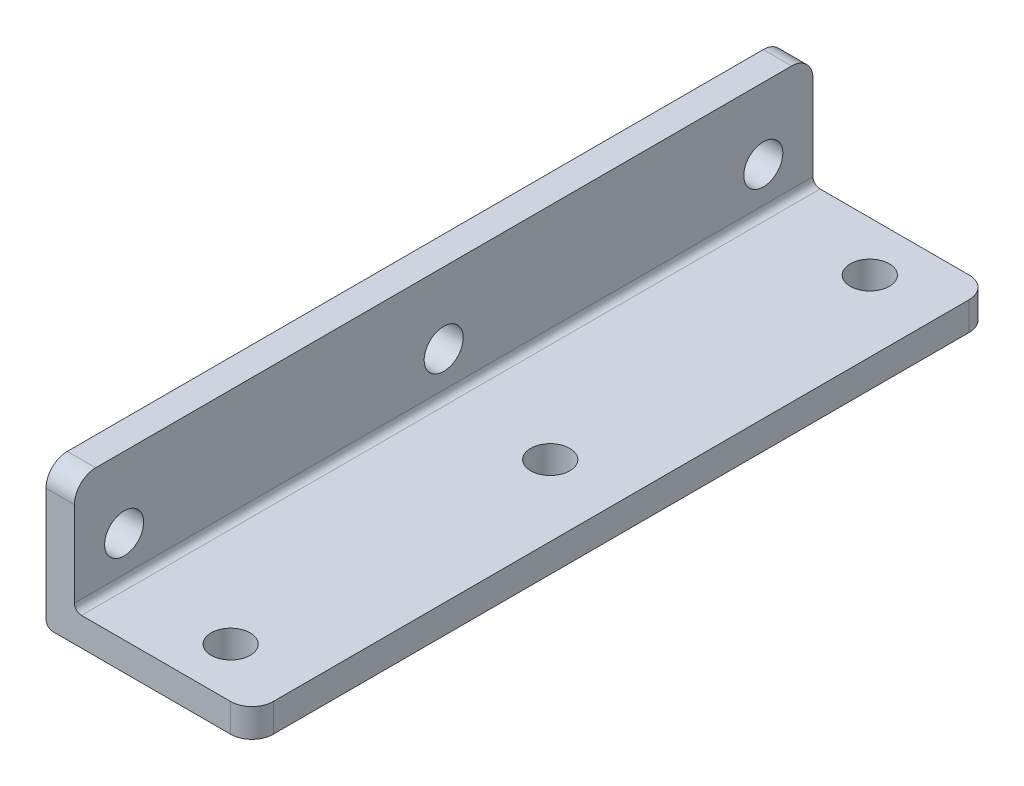
SolidWorks part; units mm, degrees
ref_plane "정면" through (0, 0, 0) normal (0, 0, 1) x (1, 0, 0)
ref_plane "윗면" through (0, 0, 0) normal (0, 1, 0) x (1, 0, 0)
ref_plane "우측면" through (0, 0, 0) normal (1, 0, 0) x (0, 0, -1)
sketch "스케치1" plane through (0, 0, 0) normal (0, 0, 1) x (1, 0, 0)
  line L1 (0, 0) -> (29, 0)
  line L2 (0, 0) -> (0, -4)
  line L3 (0, -4) -> (29, -4)
  line L4 (29, 0) -> (29, -4)
  line L5 (0, 0) -> (4, 0)
  line L6 (0, 0) -> (0, 16)
  line L7 (0, 16) -> (4, 16)
  line L8 (4, 0) -> (4, 16)
  point P8 (29, -2)
  dimension "D1" = 25
  dimension "D2" = 16
  dimension "D3" = 4
  dimension "D4" = 4
extrude "보스-돌출1" add sketch "스케치1" along normal mid plane 110 contours L4 L1 L2 L3 | L1 L8 L7 L6
sketch "스케치2" plane through (0, 0, 0) normal (0, 1, 0) x (1, 0, 0)
  line L0 (19, 55) -> (19, -55) construction
  line L1 (4, 55) -> (29, 55) construction
  line L2 (4, -55) -> (29, -55) construction
  line L3 (4, 0) -> (29, 0) construction
  line L4 (4, -55) -> (4, 55) construction
  line L5 (29, -55) -> (29, 55) construction
  circle A0 centre (19, 0) radius 2.75
  circle A1 centre (19, -45) radius 2.75
  circle A2 centre (19, 45) radius 2.75
  dimension "D1" = 5.5
  dimension "D4" = 5.5
  dimension "D5" = 5.5
  dimension "D2" = 10
  dimension "D3" = 10
  dimension "D6" = 10
sketch "스케치3" plane through (4, 0, 0) normal (1, 0, 0) x (0, 0, -1)
  line L0 (-55, 6) -> (55, 6) construction
  line L3 (0, 16) -> (0, 0) construction
  line L4 (-55, 16) -> (55, 16) construction
  line L5 (-55, 0) -> (55, 0) construction
  line L6 (-55, 0) -> (-55, 16) construction
  line L7 (55, 0) -> (55, 16) construction
  circle A0 centre (0, 6) radius 2.75
  circle A1 centre (-45, 6) radius 2.75
  circle A2 centre (45, 6) radius 2.75
  dimension "D1" = 5.5
  dimension "D2" = 10
extrude "컷-돌출3" cut sketch "스케치3" against normal blind 20
extrude "컷-돌출4" cut sketch "스케치2" against normal blind 20
fillet "필렛2" radius 1 2 edges at (0, -4, 0) (4, 0, 0)
sketch "스케치4" plane through (0, 0, 55) normal (0, 0, 1) x (1, 0, 0)
  line L6 (0, 16) -> (0, -3)
  line L7 (1, -4) -> (29, -4)
  line L8 (29, -4) -> (29, 0)
  line L9 (29, 0) -> (5, 0)
  line L10 (4, 1) -> (4, 16)
  line L11 (4, 16) -> (0, 16)
  line L12 (0, 16) -> (0, -3)
  line L13 (1, -4) -> (29, -4)
  line L14 (29, -4) -> (29, 0)
  line L15 (29, 0) -> (5, 0)
  line L16 (4, 1) -> (4, 16)
  line L17 (4, 16) -> (0, 16)
  arc A2 (0, -3) -> (1, -4) centre (1, -3) ccw
  arc A3 (4, 1) -> (5, 0) centre (5, 1) ccw
  arc A4 (0, -3) -> (1, -4) centre (1, -3) ccw
  arc A5 (4, 1) -> (5, 0) centre (5, 1) ccw
  dimension "D1" = 0
extrude "컷-돌출5" cut sketch "스케치4" against normal blind 3
sketch "스케치5" plane through (0, 0, -55) normal (0, 0, -1) x (-1, 0, 0)
  line L6 (-29, -4) -> (-1, -4)
  line L7 (0, -3) -> (0, 16)
  line L8 (0, 16) -> (-4, 16)
  line L9 (-4, 16) -> (-4, 1)
  line L10 (-5, 0) -> (-29, 0)
  line L11 (-29, 0) -> (-29, -4)
  line L12 (-29, -4) -> (-1, -4)
  line L13 (0, -3) -> (0, 16)
  line L14 (0, 16) -> (-4, 16)
  line L15 (-4, 16) -> (-4, 1)
  line L16 (-5, 0) -> (-29, 0)
  line L17 (-29, 0) -> (-29, -4)
  arc A2 (-1, -4) -> (0, -3) centre (-1, -3) ccw
  arc A3 (-5, 0) -> (-4, 1) centre (-5, 1) ccw
  arc A4 (-1, -4) -> (0, -3) centre (-1, -3) ccw
  arc A5 (-5, 0) -> (-4, 1) centre (-5, 1) ccw
  dimension "D1" = 0
extrude "컷-돌출6" cut sketch "스케치5" against normal blind 3
fillet "필렛3" radius 3 4 edges at (2, 16, -52) (29, -2, -52) (29, -2, 52) (2, 16, 52)
